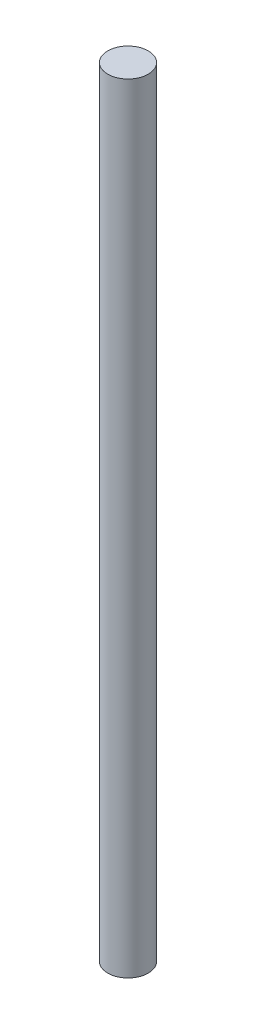
SolidWorks part; units mm, degrees
ref_plane "Front Plane" through (0, 0, 0) normal (0, 0, 1) x (1, 0, 0)
ref_plane "Top Plane" through (0, 0, 0) normal (0, 1, 0) x (1, 0, 0)
ref_plane "Right Plane" through (0, 0, 0) normal (1, 0, 0) x (0, 0, -1)
sketch "Sketch1" plane through (0, 0, 0) normal (0, 1, 0) x (1, 0, 0)
  circle A0 centre (0, 0) radius 12.5
  dimension "D1" = 25
extrude "Boss-Extrude1" add sketch "Sketch1" along normal blind 481.306
